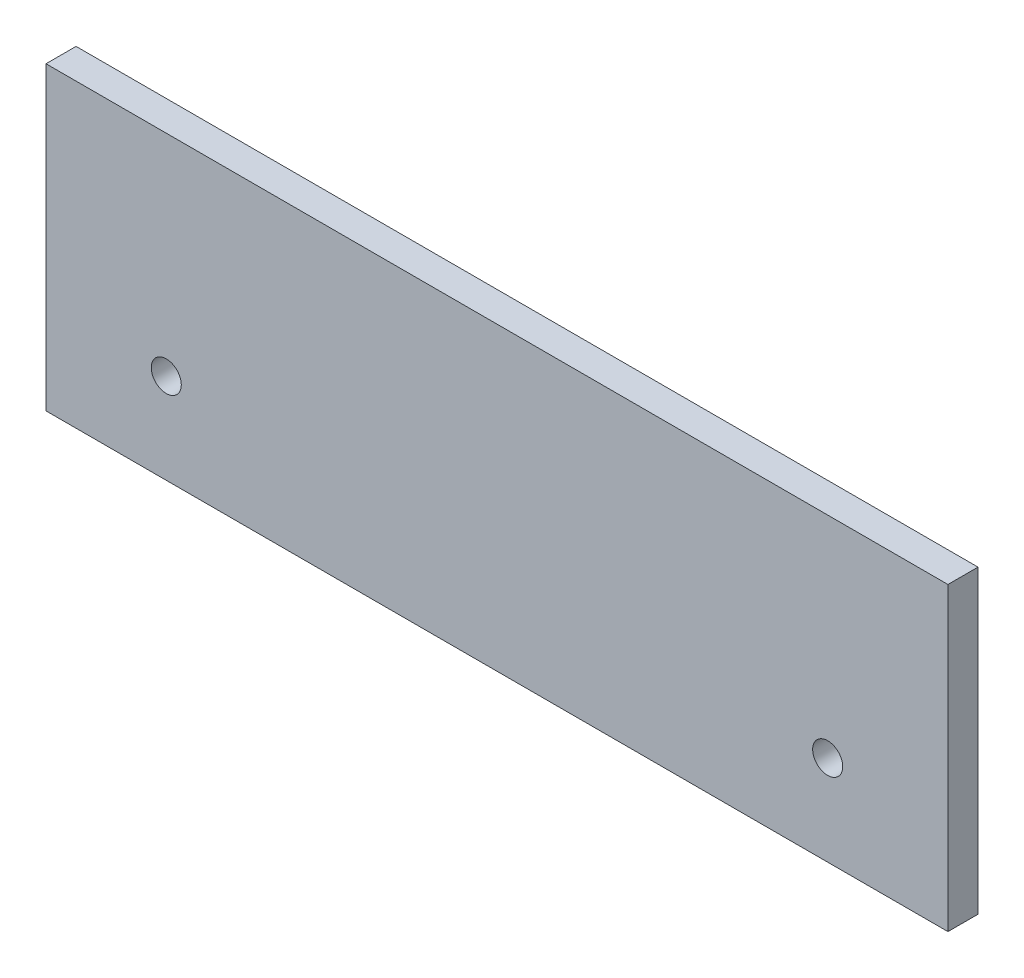
SolidWorks part; units mm, degrees
ref_plane "Plan de face" through (0, 0, 0) normal (0, 0, 1) x (1, 0, 0)
ref_plane "Plan de dessus" through (0, 0, 0) normal (0, 1, 0) x (1, 0, 0)
ref_plane "Plan de droite" through (0, 0, 0) normal (1, 0, 0) x (0, 0, -1)
sketch "Esquisse1" plane through (0, 0, 0) normal (0, 0, 1) x (1, 0, 0)
  line L0 (-182.7761, 0) -> (117.2239, 0)
  line L1 (117.2239, 0) -> (117.2239, -100)
  line L2 (117.2239, -100) -> (-182.7761, -100)
  line L3 (-182.7761, -100) -> (-182.7761, 0)
  dimension "D1" = 300
  dimension "D2" = 100
extrude "Boss.-Extru.1" add sketch "Esquisse1" along normal blind 10
sketch "Esquisse2" plane through (0, 0, 10) normal (0, 0, 1) x (1, 0, 0)
  line L0 (-182.7761, -100) -> (117.2239, -100) construction
  line L1 (-182.7761, 0) -> (-182.7761, -100) construction
  line L2 (117.2239, -100) -> (117.2239, 0) construction
  circle A0 centre (-142.7761, -70) radius 5
  circle A1 centre (77.2239, -70) radius 5
  dimension "D1" = 30
  dimension "D2" = 40
  dimension "D3" = 40
  dimension "D4" = 30
  dimension "D5" = 10
extrude "Enlèv. mat.-Extru.1" cut sketch "Esquisse2" against normal blind 10
